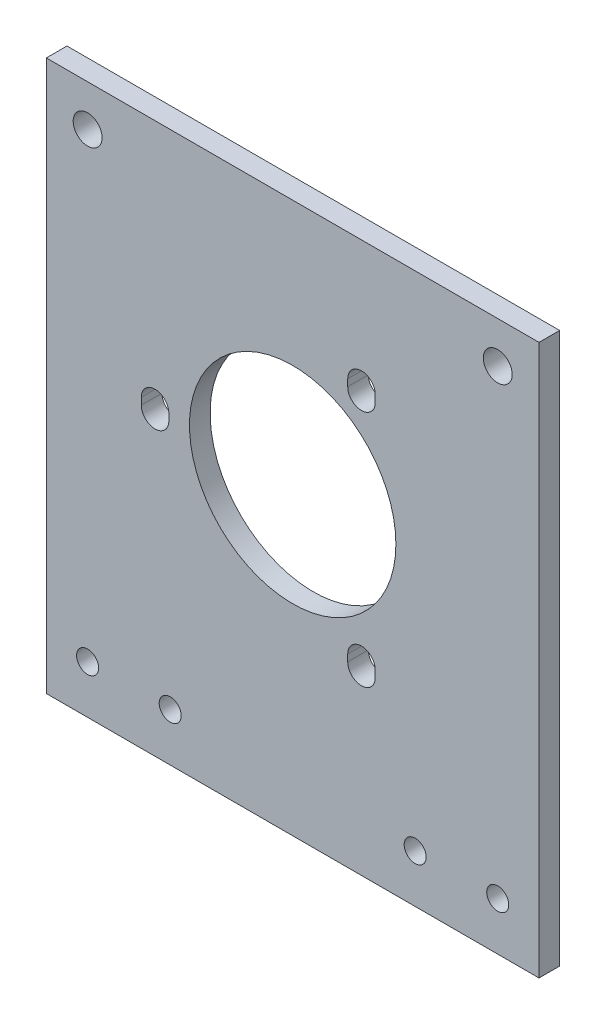
SolidWorks part; units mm, degrees
ref_plane "前视基准面" through (0, 0, 0) normal (0, 0, 1) x (1, 0, 0)
ref_plane "上视基准面" through (0, 0, 0) normal (0, 1, 0) x (1, 0, 0)
ref_plane "右视基准面" through (0, 0, 0) normal (1, 0, 0) x (0, 0, -1)
sketch "草图1" plane through (0, 0, 0) normal (0, 0, 1) x (1, 0, 0)
  line L1 (-35.8, 35.8) -> (35.8, 35.8)
  line L2 (-35.8, 35.8) -> (-35.8, -44.2)
  line L3 (-35.8, -44.2) -> (35.8, -44.2)
  line L4 (35.8, 35.8) -> (35.8, -44.2)
  arc A0 (25.3144, -25.3144) -> (-25.3144, 25.3144) centre (0, 0) ccw construction
  arc A1 (-25.3144, 25.3144) -> (25.3144, -25.3144) centre (0, 0) ccw construction
  arc A2 (11.1667, 16.1538) -> (8.8333, 18.4872) centre (10, 17.3205) ccw construction
  arc A3 (8.8333, 18.4872) -> (11.1667, 16.1538) centre (10, 17.3205) ccw construction
  arc A4 (-18.8333, -1.1667) -> (-21.1667, 1.1667) centre (-20, 0) ccw construction
  arc A5 (-21.1667, 1.1667) -> (-18.8333, -1.1667) centre (-20, 0) ccw construction
  arc A6 (11.1667, -18.4872) -> (8.8333, -16.1538) centre (10, -17.3205) ccw construction
  arc A7 (8.8333, -16.1538) -> (11.1667, -18.4872) centre (10, -17.3205) ccw construction
  arc A8 (8.8333, -16.1538) -> (11.1667, -18.4872) centre (10, -17.3205) ccw
  arc A9 (11.1667, -18.4872) -> (8.8333, -16.1538) centre (10, -17.3205) ccw
  arc A10 (-21.1667, 1.1667) -> (-18.8333, -1.1667) centre (-20, 0) ccw
  arc A11 (-18.8333, -1.1667) -> (-21.1667, 1.1667) centre (-20, 0) ccw
  arc A12 (8.8333, 18.4872) -> (11.1667, 16.1538) centre (10, 17.3205) ccw
  arc A13 (11.1667, 16.1538) -> (8.8333, 18.4872) centre (10, 17.3205) ccw
  circle A14 centre (-29.8, 29.8) radius 2.1
  circle A15 centre (29.8, 29.8) radius 2.1
  dimension "D2" = 4.2
  dimension "D3" = 6
  dimension "D4" = 6
  dimension "D5" = 6
  dimension "D6" = 6
  dimension "D1" = 80
extrude "凸台-拉伸1" add sketch "草图1" along normal blind 3
sketch "草图2" plane through (0, 0, 3) normal (0, 0, 1) x (1, 0, 0)
  circle A8 centre (29.8, -37.2) radius 1.6 construction
  circle A9 centre (17.8, -37.2) radius 1.6 construction
  circle A10 centre (-17.8, -37.2) radius 1.6 construction
  circle A11 centre (-29.8, -37.2) radius 1.6 construction
  circle A12 centre (29.8, -37.2) radius 1.6
  circle A13 centre (17.8, -37.2) radius 1.6
  circle A14 centre (-17.8, -37.2) radius 1.6
  circle A15 centre (-29.8, -37.2) radius 1.6
extrude "切除-拉伸1" cut sketch "草图2" against normal blind 3
sketch "草图3" plane through (0, 0, 3) normal (0, 0, 1) x (1, 0, 0)
  circle A0 centre (0, 0) radius 15
  dimension "D1" = 30
extrude "切除-拉伸2" cut sketch "草图3" against normal blind 3
sketch "草图4" plane through (0, 0, 3) normal (0, 0, 1) x (1, 0, 0)
  line L0 (10, 17.3205) -> (10, 16.3205) construction
  line L1 (12, 17.3205) -> (12, 16.3205)
  line L2 (8, 17.3205) -> (8, 16.3205)
  line L3 (-20, 0) -> (-20, -1) construction
  line L4 (-18, 0) -> (-18, -1)
  line L5 (-22, 0) -> (-22, -1)
  line L6 (10, -17.3205) -> (10, -18.3205) construction
  line L7 (12, -17.3205) -> (12, -18.3205)
  line L8 (8, -17.3205) -> (8, -18.3205)
  line L9 (0, 0) -> (10, 17.3205) construction
  line L10 (0, 0) -> (-20, 0) construction
  line L11 (0, 0) -> (10, -17.3205) construction
  arc A0 (12, 17.3205) -> (8, 17.3205) centre (10, 17.3205) ccw
  arc A1 (8, 16.3205) -> (12, 16.3205) centre (10, 16.3205) ccw
  arc A2 (-18, 0) -> (-22, 0) centre (-20, 0) ccw
  arc A3 (-22, -1) -> (-18, -1) centre (-20, -1) ccw
  arc A4 (12, -17.3205) -> (8, -17.3205) centre (10, -17.3205) ccw
  arc A5 (8, -18.3205) -> (12, -18.3205) centre (10, -18.3205) ccw
  circle A6 centre (0, 0) radius 20 construction
  point P3 (10, 16.8205)
  point P8 (-20, -0.5)
  point P16 (10, -17.8205)
  point P29 (10, 17.3205)
  point P32 (10, 17.3205)
  dimension "D1" = 2
  dimension "D2" = 2
  dimension "D3" = 2
  dimension "D4" = 1
  dimension "D5" = 1
  dimension "D6" = 1
extrude "切除-拉伸3" cut sketch "草图4" against normal blind 3
